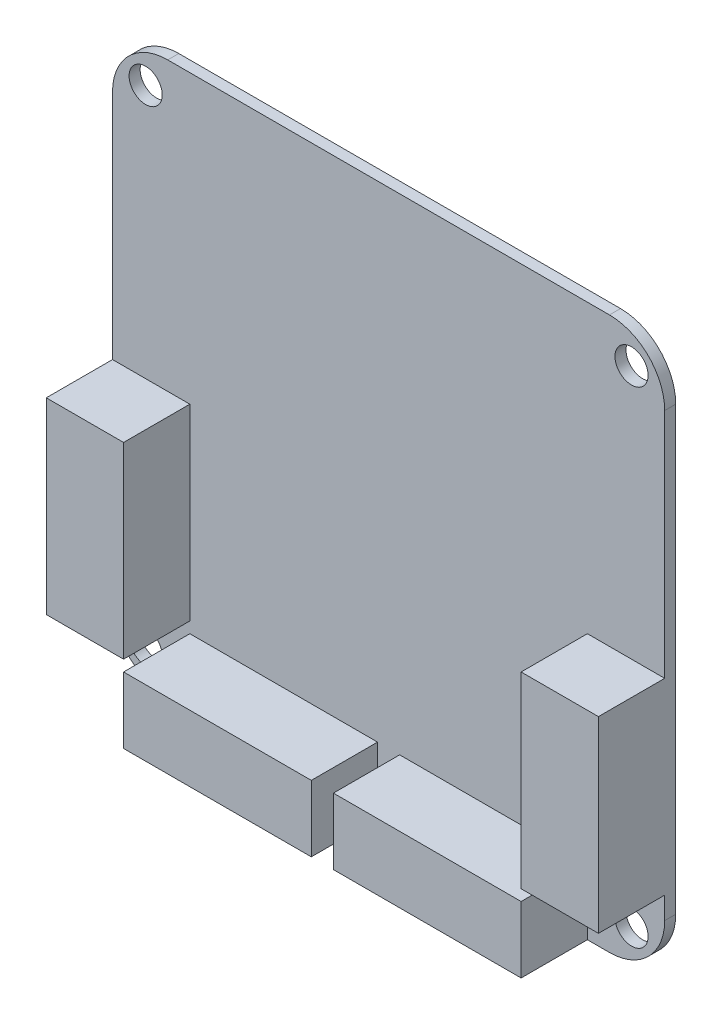
SolidWorks part; units mm, degrees
ref_plane "前视基准面" through (0, 0, 0) normal (0, 0, 1) x (1, 0, 0)
ref_plane "上视基准面" through (0, 0, 0) normal (0, 1, 0) x (1, 0, 0)
ref_plane "右视基准面" through (0, 0, 0) normal (1, 0, 0) x (0, 0, -1)
other "Configuration Table"
sketch "草图1" plane through (0, 0, 0) normal (0, 0, 1) x (1, 0, 0)
  line L1 (25, -25) -> (-25, -25)
  line L2 (25, -25) -> (25, 25)
  line L3 (25, 25) -> (-25, 25)
  line L4 (-25, -25) -> (-25, 25)
  line L5 (25, -25) -> (-25, 25) construction
  line L6 (25, 25) -> (-25, -25) construction
  point P0 (0, 0)
  dimension "D1" = 50
  dimension "D2" = 50
extrude "凸台-拉伸1" add sketch "草图1" along normal blind 1
fillet "圆角1" radius 5 4 edges at (-25, -25, 0.5) (25, -25, 0.5) (25, 25, 0.5) (-25, 25, 0.5)
sketch "草图2" plane through (0, 0, 1) normal (0, 0, 1) x (1, 0, 0)
  line L0 (0, 25) -> (0, -25) construction
  line L1 (20, 25) -> (-20, 25) construction
  line L2 (-20, -25) -> (20, -25) construction
  line L3 (-25, 20) -> (-25, -20) construction
  line L4 (-1, -25) -> (-18, -25)
  line L5 (-1, -25) -> (-1, -19)
  line L6 (-1, -19) -> (-18, -19)
  line L7 (-18, -25) -> (-18, -19)
  line L8 (-25, -18) -> (-18, -18)
  line L9 (-25, -18) -> (-25, -1)
  line L10 (-25, -1) -> (-18, -1)
  line L11 (-18, -18) -> (-18, -1)
  line L12 (1, -19) -> (18, -19)
  line L13 (18, -25) -> (18, -19)
  line L14 (1, -25) -> (18, -25)
  line L15 (1, -25) -> (1, -19)
  line L16 (25, -1) -> (18, -1)
  line L17 (18, -18) -> (18, -1)
  line L18 (25, -18) -> (18, -18)
  line L19 (25, -18) -> (25, -1)
  dimension "D1" = 17
  dimension "D2" = 7
  dimension "D3" = 17
  dimension "D4" = 1
  dimension "D5" = 0
extrude "凸台-拉伸2" add sketch "草图2" along normal blind 6
sketch "草图3" plane through (0, 0, 1) normal (0, 0, 1) x (1, 0, 0)
  line L1 (22, -22) -> (-22, -22) construction
  line L2 (22, -22) -> (22, 22) construction
  line L3 (22, 22) -> (-22, 22) construction
  line L4 (-22, -22) -> (-22, 22) construction
  line L5 (22, -22) -> (-22, 22) construction
  line L6 (22, 22) -> (-22, -22) construction
  circle A0 centre (-22, 22) radius 1.5
  circle A1 centre (22, 22) radius 1.5
  circle A2 centre (-22, -22) radius 1.5
  circle A3 centre (22, -22) radius 1.5
  point P0 (0, 0)
  dimension "D3" = 3
  dimension "D4" = 3
  dimension "D5" = 3
  dimension "D6" = 3
  dimension "D1" = 44
  dimension "D2" = 44
extrude "切除-拉伸1" cut sketch "草图3" against normal blind 10
